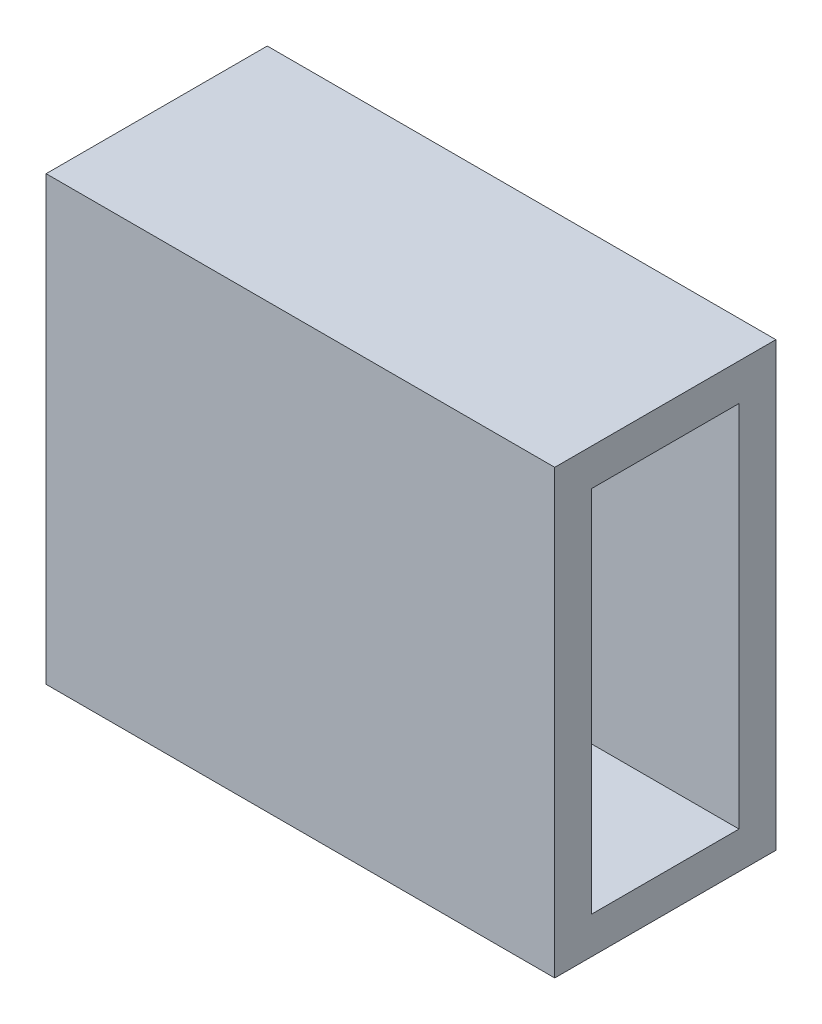
SolidWorks part; units mm, degrees
ref_plane "Front Plane" through (0, 0, 0) normal (0, 0, 1) x (1, 0, 0)
ref_plane "Top Plane" through (0, 0, 0) normal (0, 1, 0) x (1, 0, 0)
ref_plane "Right Plane" through (0, 0, 0) normal (1, 0, 0) x (0, 0, -1)
sketch "Sketch1" plane through (0, 0, 0) normal (0, 0, 1) x (1, 0, 0)
  line L4 (63.5, 38.1) -> (-63.5, 38.1)
  line L5 (63.5, -38.1) -> (63.5, 38.1)
  line L6 (-63.5, -38.1) -> (63.5, -38.1)
  line L7 (-63.5, 38.1) -> (-63.5, -38.1)
  line L8 (63.5, 38.1) -> (-63.5, 38.1)
  line L9 (63.5, -38.1) -> (63.5, 38.1)
  line L10 (-63.5, -38.1) -> (63.5, -38.1)
  line L11 (-63.5, 38.1) -> (-63.5, -38.1)
  circle A1 centre (25.4, 0) radius 12.7
  circle A2 centre (25.4, 0) radius 12.7
  dimension "D1" = 0
  dimension "D2" = 0
sketch "Sketch2" plane through (0, 0, 0) normal (0, 1, 0) x (1, 0, 0)
  line L4 (-63.5, 12.7) -> (-63.5, -25.4)
  line L5 (-63.5, -25.4) -> (63.5, -25.4)
  line L6 (63.5, -25.4) -> (63.5, 0)
  line L7 (-18.5941, 12.7) -> (-63.5, 12.7)
  line L8 (-63.5, 12.7) -> (-63.5, -25.4)
  line L9 (-63.5, -25.4) -> (63.5, -25.4)
  line L10 (63.5, -25.4) -> (63.5, 0)
  line L11 (-18.5941, 12.7) -> (-63.5, 12.7)
  arc A3 (63.5, 0) -> (25.4, 38.1) centre (25.4, 0) ccw
  arc A4 (25.4, 38.1) -> (-7.5956, 19.05) centre (25.4, 0) ccw
  arc A5 (-18.5941, 12.7) -> (-7.5956, 19.05) centre (-18.5941, 25.4) ccw
  arc A6 (63.5, 0) -> (25.4, 38.1) centre (25.4, 0) ccw
  arc A7 (25.4, 38.1) -> (-7.5956, 19.05) centre (25.4, 0) ccw
  arc A8 (-18.5941, 12.7) -> (-7.5956, 19.05) centre (-18.5941, 25.4) ccw
  dimension "D1" = 0
sketch "Sketch3" plane through (0, 0, 0) normal (0, 1, 0) x (1, 0, 0)
  line L0 (25.4, 88.9) -> (25.4, -76.2) construction
  line L1 (25.4, 88.9) -> (25.4, -76.2)
sketch "Sketch4" plane through (-152.4, 0, 0) normal (-1, 0, 0) x (0, 0, 1)
  line L8 (19.05, 31.75) -> (-6.35, 31.75)
  line L9 (-6.35, 31.75) -> (-6.35, -31.75)
  line L10 (-6.35, -31.75) -> (19.05, -31.75)
  line L11 (19.05, -31.75) -> (19.05, 31.75)
  line L12 (19.05, 31.75) -> (-6.35, 31.75)
  line L13 (-6.35, 31.75) -> (-6.35, -31.75)
  line L14 (-6.35, -31.75) -> (19.05, -31.75)
  line L15 (19.05, -31.75) -> (19.05, 31.75)
  line L16 (-12.7, 38.1) -> (-12.7, -38.1)
  line L17 (-12.7, -38.1) -> (25.4, -38.1)
  line L18 (25.4, -38.1) -> (25.4, 38.1)
  line L19 (25.4, 38.1) -> (-12.7, 38.1)
  line L20 (-12.7, 38.1) -> (-12.7, -38.1)
  line L21 (-12.7, -38.1) -> (25.4, -38.1)
  line L22 (25.4, -38.1) -> (25.4, 38.1)
  line L23 (25.4, 38.1) -> (-12.7, 38.1)
  dimension "D1" = 1.27
  dimension "D2" = 0
extrude "Boss-Extrude1" add sketch "Sketch4" against normal offset from surface (87.63 mm away) 1.27
